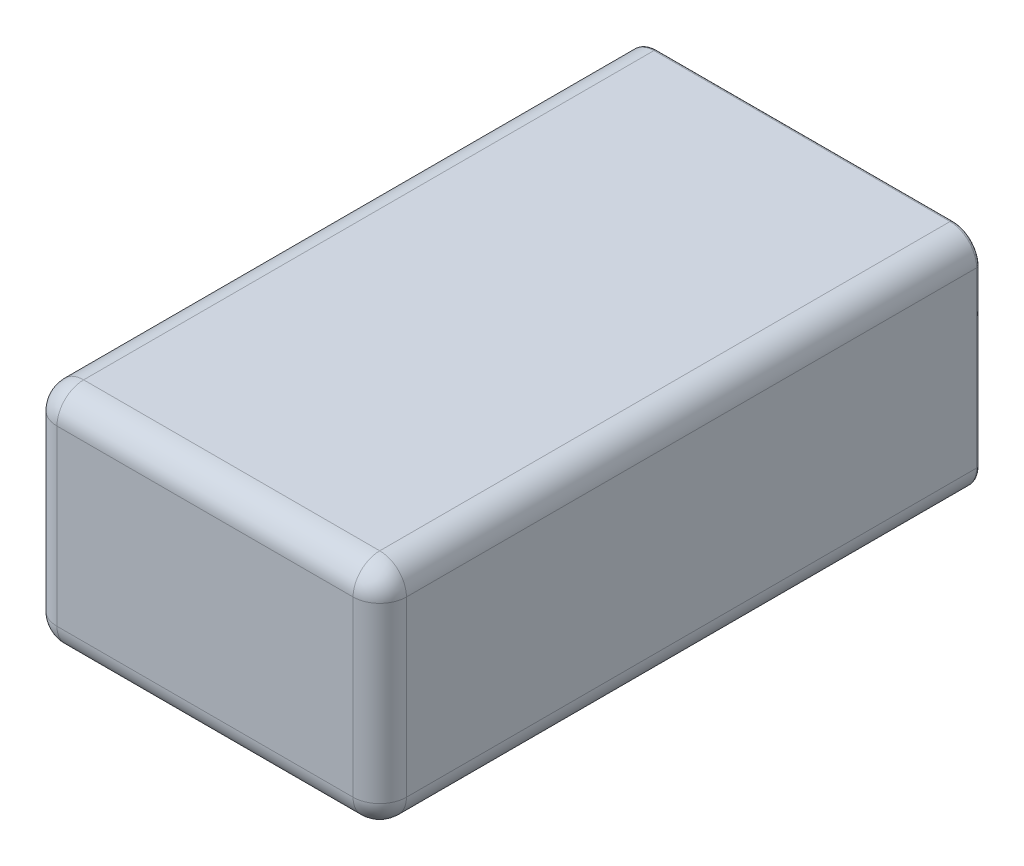
SolidWorks part; units mm, degrees
ref_plane "Plan de face" through (0, 0, 0) normal (0, 0, 1) x (1, 0, 0)
ref_plane "Plan de dessus" through (0, 0, 0) normal (0, 1, 0) x (1, 0, 0)
ref_plane "Plan de droite" through (0, 0, 0) normal (1, 0, 0) x (0, 0, -1)
sketch "Esquisse1" plane through (0, 0, 0) normal (0, 0, 1) x (1, 0, 0)
  line L0 (-16.1614, 0) -> (17.5143, 0) construction
  line L1 (0, 11.454) -> (0, -12.4041) construction
  line L3 (-11.1, 8.5) -> (11.1, 8.5)
  line L4 (-13.1, 6.5) -> (-13.1, -6.5)
  line L5 (-11.1, -8.5) -> (11.1, -8.5)
  line L6 (13.1, 6.5) -> (13.1, -6.5)
  arc A0 (-11.1, 8.5) -> (-13.1, 6.5) centre (-11.1, 6.5) ccw
  arc A1 (11.1, 8.5) -> (13.1, 6.5) centre (11.1, 6.5) cw
  arc A2 (11.1, -8.5) -> (13.1, -6.5) centre (11.1, -6.5) ccw
  arc A3 (-13.1, -6.5) -> (-11.1, -8.5) centre (-11.1, -6.5) ccw
  dimension "D3" = 2
  dimension "D1" = 26.2
  dimension "D2" = 17
extrude "Boss.-Extru.1" add sketch "Esquisse1" along normal blind 45
sketch "Esquisse2" plane through (0, 0, 0) normal (0, 0, -1) x (-1, 0, 0)
  line L24 (11.6, -6.5) -> (11.6, 6.5)
  line L25 (-11.1, -7) -> (11.1, -7)
  line L26 (-11.6, 6.5) -> (-11.6, -6.5)
  line L27 (11.1, 7) -> (-11.1, 7)
  line L28 (11.6, -6.5) -> (11.6, 6.5)
  line L29 (-11.1, -7) -> (11.1, -7)
  line L30 (-11.6, 6.5) -> (-11.6, -6.5)
  line L31 (11.1, 7) -> (-11.1, 7)
  arc A20 (11.6, 6.5) -> (11.1, 7) centre (11.1, 6.5) ccw
  arc A21 (11.1, -7) -> (11.6, -6.5) centre (11.1, -6.5) ccw
  arc A22 (-11.6, -6.5) -> (-11.1, -7) centre (-11.1, -6.5) ccw
  arc A23 (-11.1, 7) -> (-11.6, 6.5) centre (-11.1, 6.5) ccw
  arc A24 (11.6, 6.5) -> (11.1, 7) centre (11.1, 6.5) ccw
  arc A25 (11.1, -7) -> (11.6, -6.5) centre (11.1, -6.5) ccw
  arc A26 (-11.6, -6.5) -> (-11.1, -7) centre (-11.1, -6.5) ccw
  arc A27 (-11.1, 7) -> (-11.6, 6.5) centre (-11.1, 6.5) ccw
  dimension "D1" = 1.5
extrude "Enlèv. mat.-Extru.1" cut sketch "Esquisse2" against normal blind 0.5
fillet "Congé1" radius 0.25 16 edges at (-13.1, 0, 0) (-12.5142, -7.9142, 0) (0, -8.5, 0) (12.5142, -7.9142, 0) (13.1, 0, 0) (12.5142, 7.9142, 0) (0, 8.5, 0) (-12.5142, 7.9142, 0) (11.4536, 6.8536, 0) (11.6, 0, 0) (11.4536, -6.8536, 0) (0, -7, 0) (-11.4536, -6.8536, 0) (-11.6, 0, 0) (-11.4536, 6.8536, 0) (0, 7, 0)
fillet "Congé2" radius 2 8 edges at (0, 8.5, 45) (12.5142, 7.9142, 45) (13.1, 0, 45) (12.5142, -7.9142, 45) (0, -8.5, 45) (-12.5142, -7.9142, 45) (-13.1, 0, 45) (-12.5142, 7.9142, 45)
sketch "Esquisse3" plane through (0, 0, 0.5) normal (0, 0, -1) x (-1, 0, 0)
  line L0 (-14.64, 0) -> (15.29, 0) construction
  line L1 (0, 10.1038) -> (0, -9.9625) construction
  circle A0 centre (-6.25, 0) radius 1.5
  circle A1 centre (6.25, 0) radius 1.5
  dimension "D1" = 3
  dimension "D2" = 3
  dimension "D3" = 12.5
extrude "Enlèv. mat.-Extru.2" cut sketch "Esquisse3" against normal blind 1
